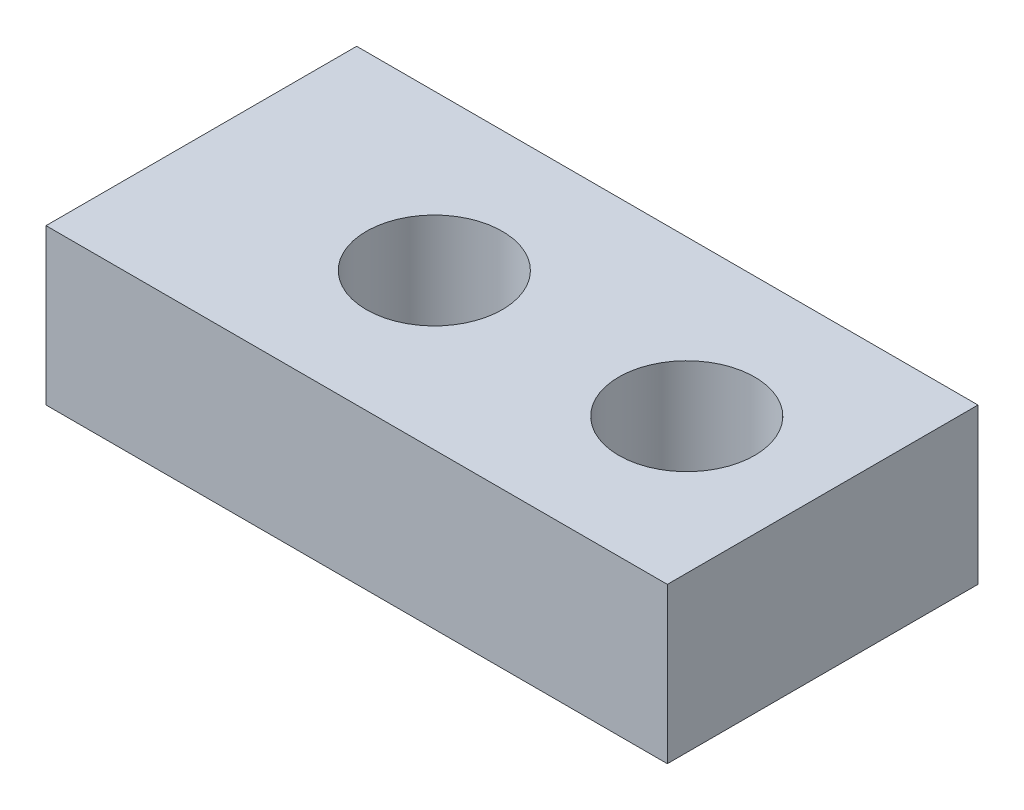
SolidWorks part; units mm, degrees
ref_plane "Front Plane" through (0, 0, 0) normal (0, 0, 1) x (1, 0, 0)
ref_plane "Top Plane" through (0, 0, 0) normal (0, 1, 0) x (1, 0, 0)
ref_plane "Right Plane" through (0, 0, 0) normal (1, 0, 0) x (0, 0, -1)
sketch "Sketch1" plane through (0, 0, 0) normal (0, 1, 0) x (1, 0, 0)
  line L1 (0, 0) -> (25.4, 0)
  line L2 (0, 0) -> (0, 12.7)
  line L3 (0, 12.7) -> (25.4, 12.7)
  line L4 (25.4, 0) -> (25.4, 12.7)
  dimension "D1" = 25.4
  dimension "D2" = 12.7
extrude "Boss-Extrude2" add sketch "Sketch1" along normal blind 6.35
sketch "Sketch2" plane through (0, 6.35, 0) normal (0, 1, 0) x (1, 0, 0)
  line L0 (25.4, 0) -> (25.4, 12.7) construction
  circle A0 centre (19.8438, 6.35) radius 2.7781
  circle A1 centre (9.525, 6.35) radius 2.7781
  dimension "D3" = 5.5562
  dimension "D4" = 5.5562
  dimension "D1" = 5.5562
  dimension "D2" = 10.3187
extrude "Cut-Extrude1" cut sketch "Sketch2" against normal blind 6.35
